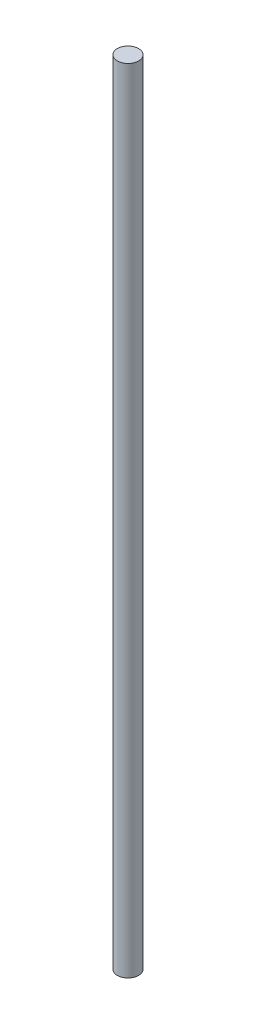
SolidWorks part; units mm, degrees
ref_plane "Front Plane" through (0, 0, 0) normal (0, 0, 1) x (1, 0, 0)
ref_plane "Top Plane" through (0, 0, 0) normal (0, 1, 0) x (1, 0, 0)
ref_plane "Right Plane" through (0, 0, 0) normal (1, 0, 0) x (0, 0, -1)
sketch "Sketch1" plane through (0, 0, 0) normal (0, 1, 0) x (1, 0, 0)
  circle A0 centre (0, 0) radius 3.175
  dimension "D1" = 6.35
extrude "Boss-Extrude1" add sketch "Sketch1" along normal blind 234.95 contours A0
equation "\"L\"= \"RodLength@J3Rod.sldasm\""
equation "\"D1@Boss-Extrude1\"=\"RodMax\""
equation "\"centerBotDist\"= 5 / 8"
equation "\"RodMax\"= \"L\" - 2 * \"centerBotDist\""
equation "\"Wiggle\"= .125"
equation "\"ThreadRodLength\"= \"RodMax\" - \"Wiggle\""
